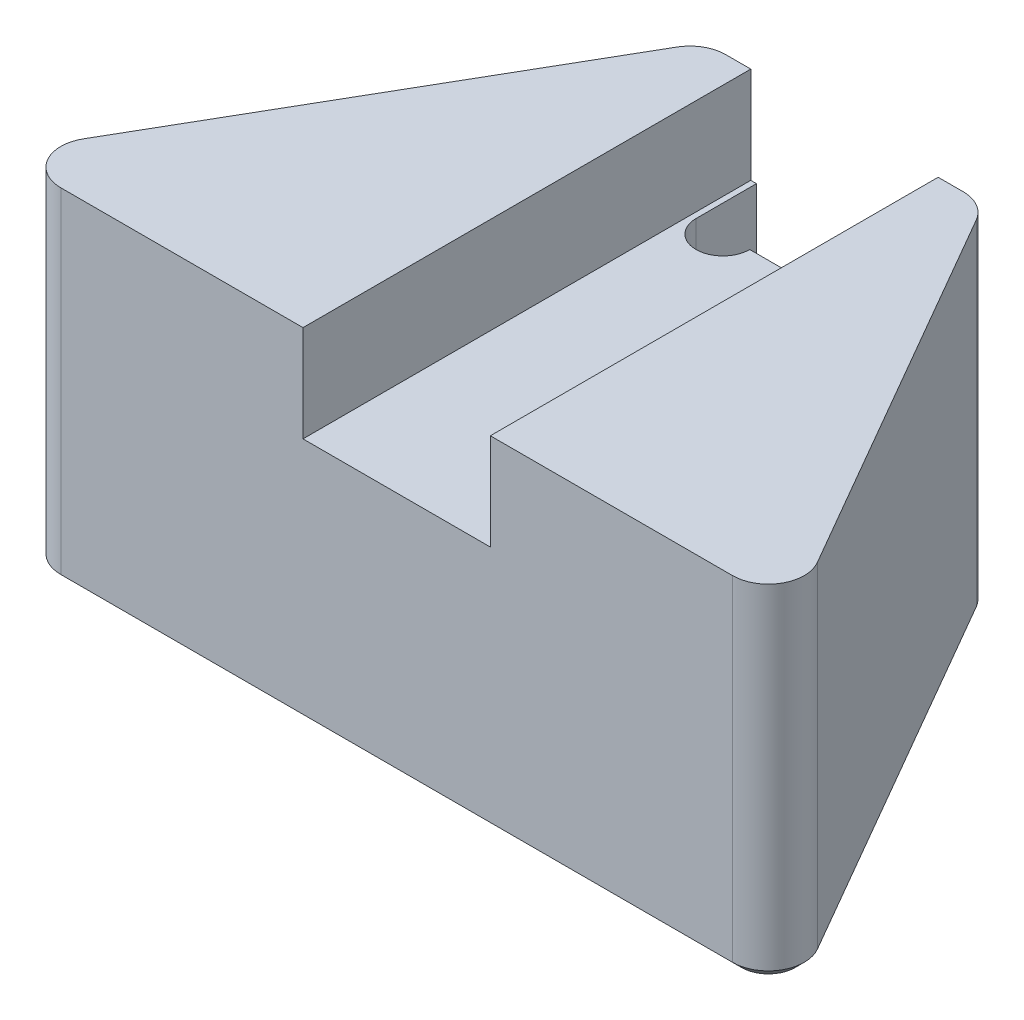
SolidWorks part; units mm, degrees
material "Macor"
ref_plane "Front Plane" through (0, 0, 0) normal (0, 0, 1) x (1, 0, 0)
ref_plane "Top Plane" through (0, 0, 0) normal (0, 1, 0) x (1, 0, 0)
ref_plane "Right Plane" through (0, 0, 0) normal (1, 0, 0) x (0, 0, -1)
sketch "Sketch1" plane through (0, 0, 0) normal (0, 1, 0) x (1, 0, 0)
  line L1 (-14.2978, -12.5) -> (14.2978, -12.5)
  line L2 (-14.2978, -12.5) -> (-14.2978, 12.5) construction
  line L3 (-14.2978, 12.5) -> (14.2978, 12.5) construction
  line L4 (14.2978, -12.5) -> (14.2978, 12.5) construction
  line L5 (-14.2978, -12.5) -> (14.2978, 12.5) construction
  line L6 (-14.2978, 12.5) -> (14.2978, -12.5) construction
  line L8 (-7.7831, 12.5) -> (7.7831, 12.5)
  line L11 (0, 11.2271) -> (0, -49988.7729) construction
  line L14 (-7.7831, 12.5) -> (-22.2169, -12.5)
  line L15 (-22.2169, -12.5) -> (-14.2978, -12.5)
  line L16 (7.7831, 12.5) -> (22.2169, -12.5)
  line L17 (22.2169, -12.5) -> (14.2978, -12.5)
  line L24 (15, 0) -> (-15, 0) construction
  point P0 (0, 0)
  point P14 (0, 12.5)
  dimension "D1" = 25
  dimension "D2" = 30
  dimension "D4" = 60
extrude "Boss-Extrude1" add sketch "Sketch1" along normal mid plane 19.2
ref_plane "Plane1" [suppressed] through (12.8676, 0, -7.7206) normal (0.8575, 0, -0.5145) x (-0.5145, 0, -0.8575)
sketch "Sketch8" [suppressed] plane through (12.8676, 0, -7.7206) normal (0.8575, 0, -0.5145) x (-0.5145, 0, -0.8575)
  line L0 (5.5737, -10.325) -> (15.8636, -10.325) construction
  line L1 (-23.5811, 10.325) -> (5.5737, 10.325)
  line L2 (-23.5811, 10.325) -> (-23.5811, -10.325)
  line L3 (-23.5811, -10.325) -> (5.5737, -10.325)
  line L4 (5.5737, 10.325) -> (5.5737, -10.325)
sketch "Sketch5" [suppressed] plane through (0, 10.325, 0) normal (0, 1, 0) x (1, 0, 0)
  line L0 (-13.9562, 2.5) -> (-14.6634, 3.2071) construction
  line L1 (-13.9562, 2.5) -> (-13.9562, 5.5) construction
  line L2 (-13.9562, 2.5) -> (-15, 2.5) construction
  line L3 (0, 0) -> (0, 50000) construction
  circle A0 centre (-14.6634, 3.2071) radius 1
  circle A1 centre (14.6634, 3.2071) radius 1
  point P2 (-13.9562, 3.9142)
  point P3 (-15.3705, 2.5)
  point P4 (-13.9562, 2.5)
  dimension "D1" = 2
  dimension "D2" = 45
extrude "Cut-Extrude5" [suppressed] cut sketch "Sketch5" against normal through all both and the other way through all
fillet "Fillet5" radius 2 4 edges at (22.2169, 0, 12.5) (-22.2169, 0, 12.5) (-7.7831, 0, -12.5) (7.7831, 0, -12.5)
sketch "Sketch6" [suppressed] plane through (0, 10.325, 0) normal (0, 1, 0) x (1, 0, 0)
  line L1 (-14.054, 4) -> (-7.5, 4)
  line L2 (-7.5, 4) -> (-7.5, 1)
  line L3 (-7.5, 1) -> (-16, 1)
  line L5 (-15.1213, 2.3181) -> (-16, 1)
  line L6 (-15.1213, 2.3181) -> (-22.9271, -9.3906) construction
  line L8 (22.9271, -9.3906) -> (15.1213, 2.3181) construction
  line L9 (16, 1) -> (15.1213, 2.3181)
  line L10 (14.054, 4) -> (7.5, 4)
  line L11 (7.5, 4) -> (7.5, 1)
  line L12 (7.5, 1) -> (16, 1)
  line L13 (9.2062, 12.5) -> (-9.2062, 12.5) construction
  arc A0 (-15.1213, 2.3181) -> (-13.9562, 3.9142) centre (-14.6634, 3.2071) ccw construction
  arc A1 (13.9562, 3.9142) -> (15.1213, 2.3181) centre (14.6634, 3.2071) ccw construction
  arc A2 (-14.054, 4) -> (-15.1213, 2.3181) centre (-14.6634, 3.2071) cw
  arc A3 (14.054, 4) -> (15.1213, 2.3181) centre (14.6634, 3.2071) ccw
  dimension "D1" = 8.5
  dimension "D2" = 15
  dimension "D3" = 3
extrude "Boss-Extrude2" [suppressed] add sketch "Sketch6" along normal blind 2
sketch "Sketch7" plane through (0, 0, 12.5) normal (0, 0, 1) x (1, 0, 0)
  line L0 (-18.7528, 9.6) -> (18.7528, 9.6) construction
  line L1 (-5.23, 9.6) -> (5.23, 9.6)
  line L2 (-5.23, 9.6) -> (-5.23, 4.22)
  line L3 (-5.23, 4.22) -> (5.23, 4.22)
  line L4 (5.23, 9.6) -> (5.23, 4.22)
  point P6 (0, 9.6)
  point P7 (0, 9.6)
  dimension "D1" = 10.46
  dimension "D2" = 5.38
extrude "Cut-Extrude6" cut sketch "Sketch7" against normal through all
sketch "Sketch9" plane through (0, 0, -12.5) normal (0, 0, -1) x (-1, 0, 0)
  line L1 (-3.175, 4.22) -> (3.175, 4.22)
  line L2 (-3.175, 4.22) -> (-3.175, -2.13)
  line L3 (-3.175, -2.13) -> (3.175, -2.13)
  line L4 (3.175, 4.22) -> (3.175, -2.13)
  line L6 (5.23, 4.22) -> (-5.23, 4.22) construction
  point P14 (0, 4.22)
  dimension "D1" = 6.35
extrude "Cut-Extrude7" [suppressed] cut sketch "Sketch9" against normal blind 2.5876
sketch "Sketch10" [suppressed] plane through (0, 0, -12.5) normal (0, 0, -1) x (-1, 0, 0)
  line L1 (-3.9751, 7.55) -> (3.9751, 7.55)
  line L2 (-3.9751, 7.55) -> (-3.9751, 1.2)
  line L3 (-3.9751, 1.2) -> (3.9751, 1.2)
  line L4 (3.9751, 7.55) -> (3.9751, 1.2)
  line L7 (3.175, 7.55) -> (-3.175, 7.55) construction
  line L9 (-3.175, 1.2) -> (3.175, 1.2) construction
  point P9 (0, 1.2)
  dimension "D1" = 7.9502
extrude "Cut-Extrude8" [suppressed] cut sketch "Sketch10" against normal blind 1.0001
sketch "Sketch11" plane through (0, 0, -12.5) normal (0, 0, -1) x (-1, 0, 0)
  line L0 (5.23, 4.22) -> (-5.23, 4.22) construction
  line L1 (-4.9125, 4.22) -> (4.9125, 4.22)
  line L2 (-4.9125, 4.22) -> (-4.9125, -5.605)
  line L3 (-4.9125, -5.605) -> (4.9125, -5.605)
  line L4 (4.9125, 4.22) -> (4.9125, -5.605)
  point P6 (0, 4.22)
  point P7 (0, 4.22)
  dimension "D1" = 9.825
extrude "Cut-Extrude9" cut sketch "Sketch11" against normal blind 3.375
fillet "Fillet6" [suppressed] radius 1.5
sketch "Sketch12" plane through (0, 4.22, 0) normal (0, 1, 0) x (1, 0, 0)
  line L0 (-4.9125, 9.125) -> (4.9125, 9.125) construction
  circle A0 centre (3.4125, 9.125) radius 1.5
  circle A1 centre (-3.4125, 9.125) radius 1.5
  dimension "D1" = 3
extrude "Cut-Extrude10" cut sketch "Sketch12" against normal up to surface (9.825 mm away) up to face at (0, -5.605, -10.8125)
chamfer "Chamfer1" distance 0.5 angle 45 8 edges at (-20.4848, -9.6, 11.5) (0, -9.6, 12.5) (20.4848, -9.6, 11.5) (14.4226, -9.6, -1) (7.6284, -9.6, -12.2321) (0, -9.6, -12.5) (-7.6284, -9.6, -12.2321) (-14.4226, -9.6, -1)
equation "\"panel_width\"= 5.5in"
equation "\"finger_joint_width\"= 30mm"
